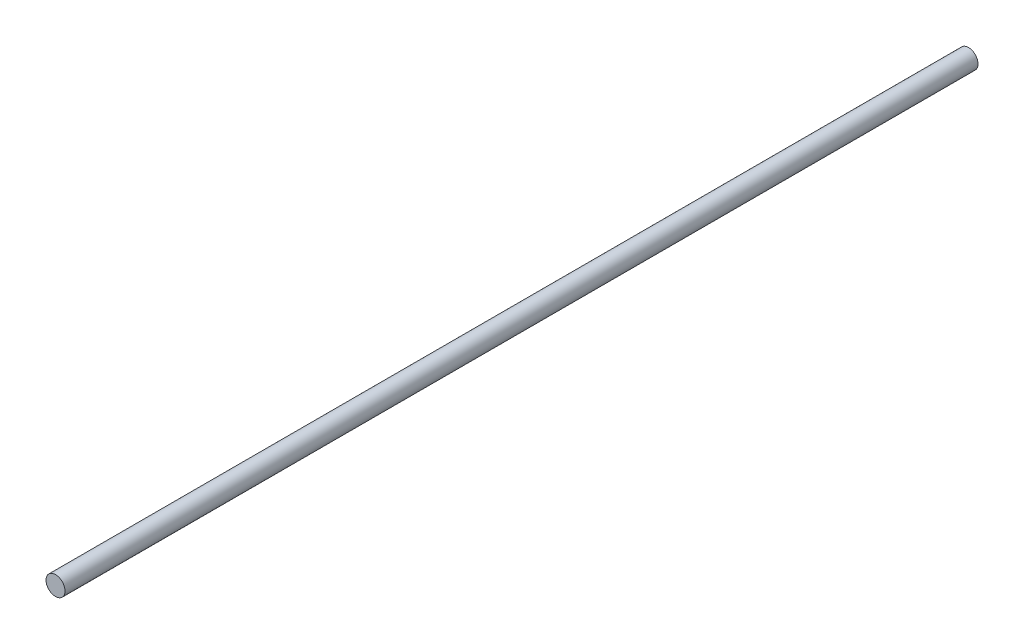
SolidWorks part; units mm, degrees
ref_plane "Front Plane" through (0, 0, 0) normal (0, 0, 1) x (1, 0, 0)
ref_plane "Top Plane" through (0, 0, 0) normal (0, 1, 0) x (1, 0, 0)
ref_plane "Right Plane" through (0, 0, 0) normal (1, 0, 0) x (0, 0, -1)
sketch "Sketch1" plane through (0, 0, 0) normal (0, 0, 1) x (1, 0, 0)
  circle A0 centre (0, 0) radius 3.175
  dimension "D1" = 6.35
extrude "Boss-Extrude1" add sketch "Sketch1" along normal blind 304.8
cosmetic thread "Cosmetic Thread4"
cosmetic thread "Cosmetic Thread8"
